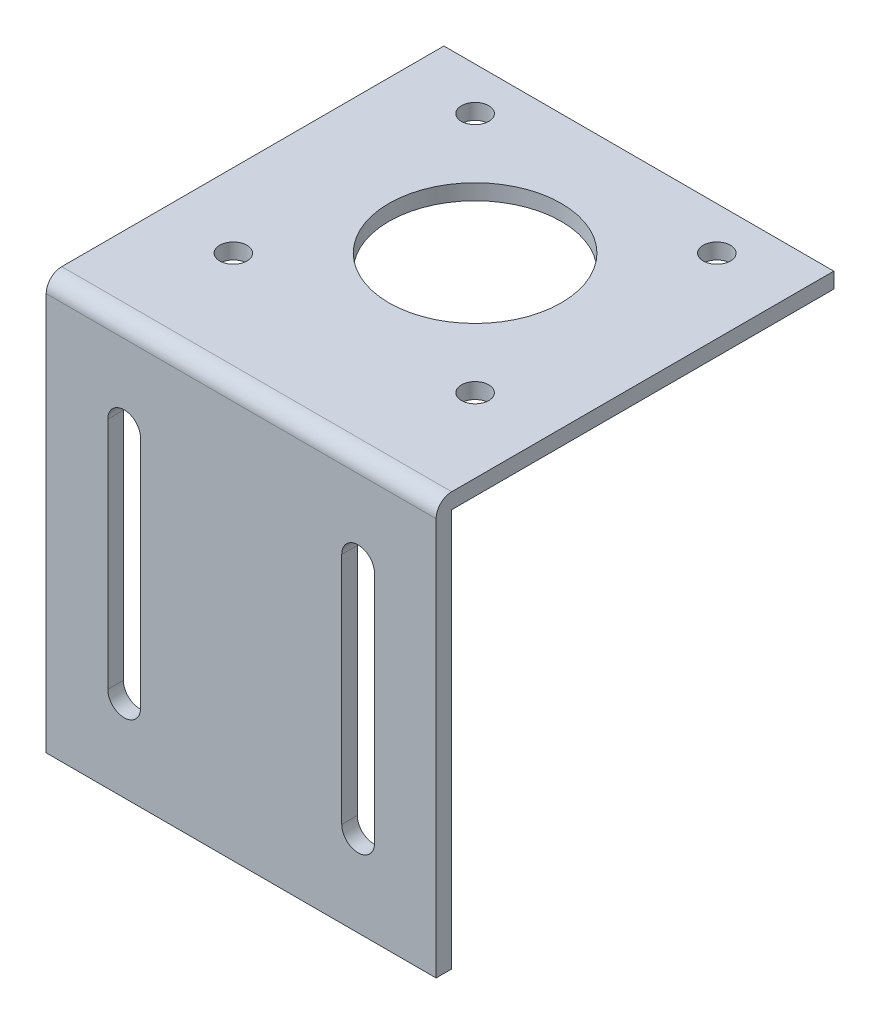
SolidWorks part; units mm, degrees
ref_plane "前视基准面" through (0, 0, 0) normal (0, 0, 1) x (1, 0, 0)
ref_plane "上视基准面" through (0, 0, 0) normal (0, 1, 0) x (1, 0, 0)
ref_plane "右视基准面" through (0, 0, 0) normal (1, 0, 0) x (0, 0, -1)
sketch "草图1" plane through (0, 0, 0) normal (0, 1, 0) x (1, 0, 0)
  line L0 (-25, 24.5) -> (-25, 3.5) construction
  line L1 (-50, 24.5) -> (0, 24.5)
  line L2 (-50, 24.5) -> (-50, -24.5)
  line L3 (-50, -24.5) -> (0, -24.5)
  line L4 (0, 24.5) -> (0, -24.5)
  line L5 (-25, 3.5) -> (-40.5, 3.5) construction
  line L6 (-40.5, 3.5) -> (-40.5, 19) construction
  line L7 (-40.5, 3.5) -> (-40.5, -12) construction
  line L8 (-25, 3.5) -> (-9.5, 3.5) construction
  line L9 (-9.5, 3.5) -> (-9.5, 19) construction
  line L10 (-9.5, 3.5) -> (-9.5, -12) construction
  circle A0 centre (-25, 3.5) radius 11.05
  circle A1 centre (-40.5, 19) radius 1.75
  circle A2 centre (-9.5, 19) radius 1.75
  circle A3 centre (-9.5, -12) radius 1.75
  circle A4 centre (-40.5, -12) radius 1.75
  point P4 (0, 0)
  dimension "D4" = 22.1
  dimension "D11" = 3.5
  dimension "D12" = 3.5
  dimension "D13" = 3.5
  dimension "D14" = 3.5
  dimension "D1" = 49
  dimension "D2" = 50
  dimension "D3" = 21
  dimension "D5" = 15.5
  dimension "D6" = 15.5
  dimension "D7" = 15.5
  dimension "D8" = 15.5
  dimension "D9" = 15.5
  dimension "D10" = 15.5
extrude "凸台-拉伸1" add sketch "草图1" along normal blind 2
sketch "草图2" plane through (0, 0, 24.5) normal (0, 0, 1) x (1, 0, 0)
  line L0 (-25, -51) -> (-25, -40) construction
  line L1 (-25, -40) -> (-10, -40) construction
  line L2 (0, 0) -> (0, -51)
  line L3 (0, -51) -> (-50, -51)
  line L4 (-50, 0) -> (-50, -51)
  line L5 (0, 0) -> (0, 2)
  line L6 (0, 2) -> (-50, 2)
  line L7 (-50, 0) -> (-50, 2)
  line L8 (-7.9, -10) -> (-7.9, -40)
  line L9 (-10, -40) -> (-10, -10) construction
  line L10 (-25, -40) -> (-40, -40) construction
  line L11 (-12.1, -10) -> (-12.1, -40)
  line L12 (-40, -40) -> (-40, -10) construction
  line L13 (-37.9, -10) -> (-37.9, -40)
  line L14 (-42.1, -10) -> (-42.1, -40)
  arc A0 (-12.1, -10) -> (-7.9, -10) centre (-10, -10) cw
  arc A1 (-42.1, -10) -> (-37.9, -10) centre (-40, -10) cw
  arc A2 (-7.9, -40) -> (-12.1, -40) centre (-10, -40) cw
  arc A3 (-37.9, -40) -> (-42.1, -40) centre (-40, -40) cw
  dimension "D9" = 2.1
  dimension "D10" = 2.1
  dimension "D11" = 2.1
  dimension "D12" = 2.1
  dimension "D1" = 50
  dimension "D2" = 51
  dimension "D3" = 2
  dimension "D4" = 11
  dimension "D5" = 15
  dimension "D6" = 15
  dimension "D7" = 30
  dimension "D8" = 30
extrude "凸台-拉伸2" add sketch "草图2" along normal blind 2
fillet "圆角2" radius 2 1 edges at (-25, 2, 26.5)
